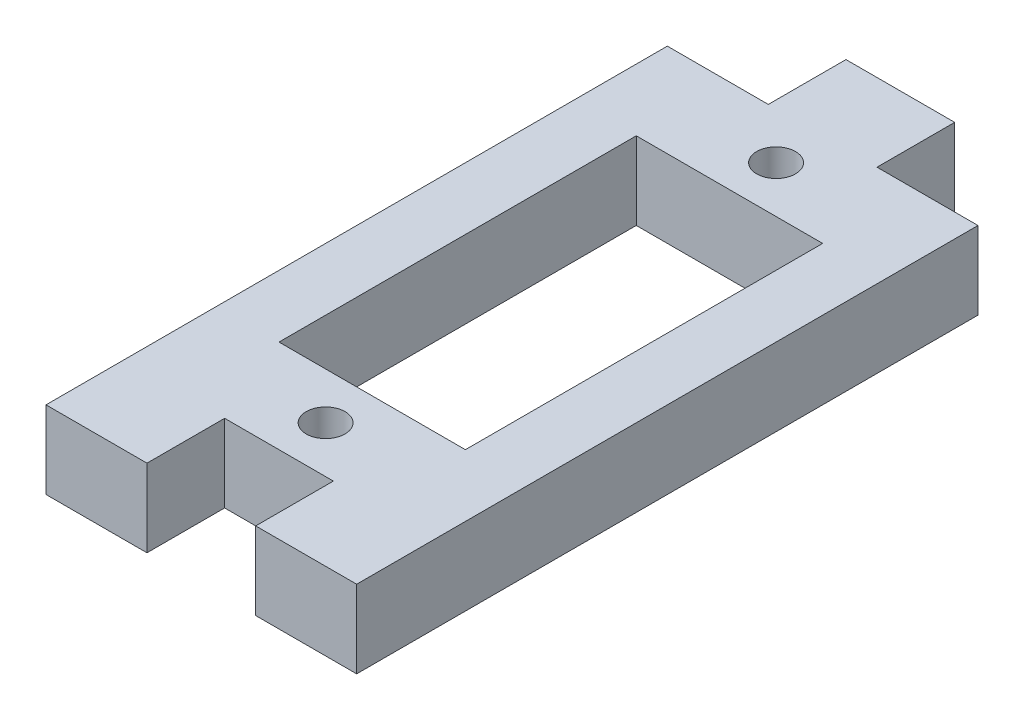
SolidWorks part; units mm, degrees
material "Acrylic (Medium-high impact)"
ref_plane "Front Plane" through (0, 0, 0) normal (0, 0, 1) x (1, 0, 0)
ref_plane "Top Plane" through (0, 0, 0) normal (0, 1, 0) x (1, 0, 0)
ref_plane "Right Plane" through (0, 0, 0) normal (1, 0, 0) x (0, 0, -1)
sketch "Sketch1" plane through (0, 0, 0) normal (0, 1, 0) x (1, 0, 0)
  line L0 (-10, 20) -> (-10, -20)
  line L1 (-10, -20) -> (-3.5, -20)
  line L2 (10, -20) -> (10, 20)
  line L3 (10, 20) -> (3.5, 20)
  line L4 (-3.5, 20) -> (-3.5, 25)
  line L5 (-3.5, 25) -> (3.5, 25)
  line L6 (3.5, 25) -> (3.5, 20)
  line L7 (-3.5, 20) -> (-10, 20)
  line L8 (-3.5, -20) -> (-3.5, -15)
  line L9 (-3.5, -15) -> (3.5, -15)
  line L10 (3.5, -15) -> (3.5, -20)
  line L11 (3.5, -20) -> (10, -20)
  point P12 (0, -15)
  point P13 (0, 25)
  point P18 (-10, 0)
  dimension "D1" = 45
  dimension "D2" = 5
  dimension "D3" = 5
  dimension "D4" = 7
  dimension "D5" = 20
  dimension "D6" = 10
extrude "Boss-Extrude1" add sketch "Sketch1" along normal blind 5
sketch "Sketch2" plane through (0, 5, 0) normal (0, 1, 0) x (1, 0, 0)
  line L0 (10, 20) -> (3.5, 20) construction
  line L1 (-6, 14) -> (6, 14)
  line L2 (-6, 14) -> (-6, -9)
  line L3 (-6, -9) -> (6, -9)
  line L4 (6, 14) -> (6, -9)
  line L5 (-6, 14) -> (6, -9) construction
  line L6 (-6, -9) -> (6, 14) construction
  line L7 (-3.5, -15) -> (3.5, -15) construction
  line L8 (0, 17) -> (0, -12) construction
  line L9 (-3.5, 20) -> (-10, 20) construction
  circle A0 centre (0, 17) radius 1.25
  circle A1 centre (0, -12) radius 1.25
  point P0 (0, 2.5)
  point P7 (0, -9)
  point P10 (0, -15)
  dimension "D6" = 2.5
  dimension "D1" = 23
  dimension "D2" = 12
  dimension "D3" = 6
  dimension "D4" = 29
  dimension "D5" = 3
extrude "Cut-Extrude1" cut sketch "Sketch2" against normal blind 5
